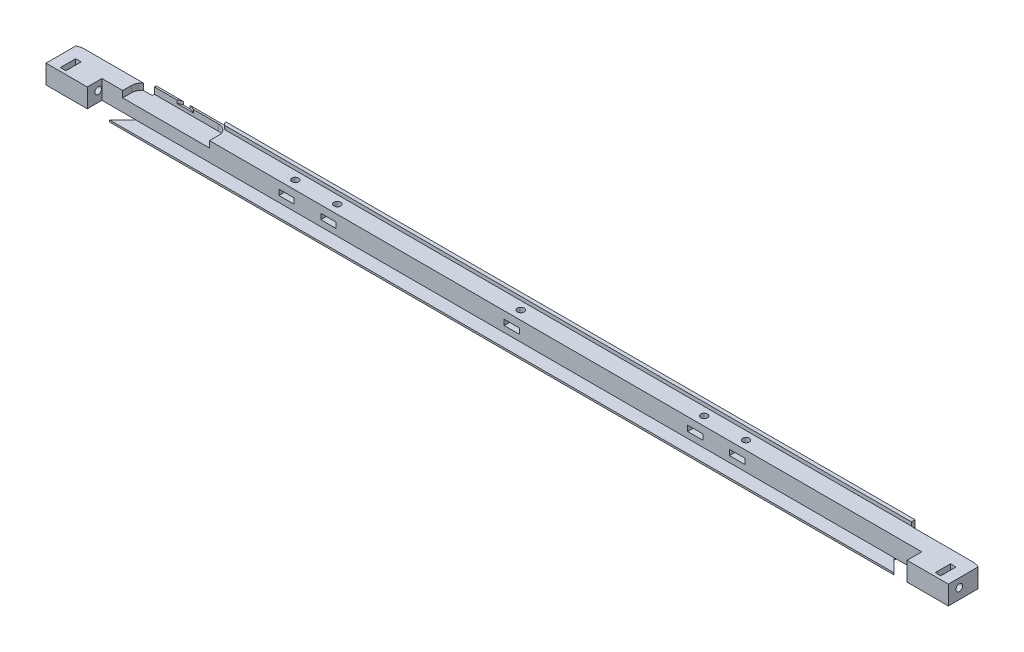
SolidWorks part; units mm, degrees
ref_plane "Front Plane" through (0, 0, 0) normal (0, 0, 1) x (1, 0, 0)
ref_plane "Top Plane" through (0, 0, 0) normal (0, 1, 0) x (1, 0, 0)
ref_plane "Right Plane" through (0, 0, 0) normal (1, 0, 0) x (0, 0, -1)
sketch "Sketch1" plane through (0, 0, 0) normal (0, 1, 0) x (1, 0, 0)
  line L0 (-134.1, 0) -> (134.1, 0)
  line L1 (134.1, 0) -> (134.1, -4.8)
  line L2 (134.1, -4.8) -> (147.6, -4.8)
  line L4 (145.3, 5.5) -> (125.16, 5.5)
  line L5 (125.16, 5.5) -> (125.16, 6.8)
  line L6 (125.16, 6.8) -> (-123.16, 6.8)
  line L7 (-123.16, 6.8) -> (-123.16, 5.5)
  line L8 (-123.16, 5.5) -> (-145.3, 5.5)
  line L10 (-147.6, -4.8) -> (-134.1, -4.8)
  line L11 (-134.1, -4.8) -> (-134.1, 0)
  line L12 (-147.6, 4.8988) -> (-147.6, -4.8)
  line L13 (147.6, 4.8988) -> (147.6, -4.8)
  line L14 (0, 6.8) -> (0, 0) construction
  line L15 (151.3, 6.8) -> (-151.3, 6.8) construction
  line L16 (151.3, 6.8) -> (151.3, -150.8147) construction
  line L17 (151.3, -150.8147) -> (-151.3, -150.8147) construction
  line L18 (-151.3, 6.8) -> (-151.3, -150.8147) construction
  line L19 (125.26, -0.1) -> (125.26, 5.5) construction
  line L20 (125.26, -0.1) -> (129.46, -4.3) construction
  line L21 (129.46, -4.3) -> (129.46, -13.8397) construction
  line L22 (-127.46, -33.4478) -> (-127.46, -4.3) construction
  line L23 (-127.46, -4.3) -> (-123.26, -0.1) construction
  line L24 (-123.26, -0.1) -> (-123.26, 5.5) construction
  arc A0 (145.3, 5.5) -> (147.6, 4.8988) centre (145.3, 0.8) cw
  arc A1 (-145.3, 5.5) -> (-147.6, 4.8988) centre (-145.3, 0.8) ccw
  dimension "D6" = 4.7
  dimension "D1" = 268.2
  dimension "D2" = 6.8
  dimension "D3" = 1.3
  dimension "D4" = 11.6
  dimension "D7" = 302.6
  dimension "D5" = 3.7
  dimension "D8" = 6
  dimension "D9" = 6
  dimension "D11" = 21.84
  dimension "D12" = 4.2
  dimension "D10" = 135
  dimension "D13" = 0.1
  dimension "D14" = 0.1
  dimension "D15" = 135
  dimension "D16" = 0.1
  dimension "D17" = 4.2
  dimension "D18" = 23.84
  dimension "D19" = 0.1
extrude "Boss-Extrude1" add sketch "Sketch1" along normal blind 8
sketch "Sketch2" plane through (0, 0, 0) normal (0, -1, 0) x (1, 0, 0)
  line L1 (125.16, -5.5) -> (147.6, -5.5)
  line L2 (125.16, -5.5) -> (125.16, 4.8)
  line L3 (125.16, 4.8) -> (147.6, 4.8)
  line L4 (147.6, -5.5) -> (147.6, 4.8)
extrude "Cut-Extrude1" cut sketch "Sketch2" against normal blind 0.6
sketch "Sketch3" plane through (0, 0, 0) normal (0, -1, 0) x (1, 0, 0)
  line L1 (-123.16, -5.5) -> (-147.6, -5.5)
  line L2 (-123.16, -5.5) -> (-123.16, 4.8)
  line L3 (-123.16, 4.8) -> (-147.6, 4.8)
  line L4 (-147.6, -5.5) -> (-147.6, 4.8)
extrude "Cut-Extrude2" cut sketch "Sketch3" against normal up to surface (0.6 mm away) up to face at (137.0084, 0.6, -0.9209)
sketch "Sketch4" plane through (0, 0, 0) normal (0, -1, 0) x (1, 0, 0)
  line L0 (129.3186, 4.3) -> (125.16, 0.1414)
  line L1 (125.16, 0.1414) -> (125.16, 0)
  line L2 (125.16, 0) -> (-123.16, 0)
  line L3 (-123.16, 0) -> (-123.16, 0.1414)
  line L4 (-123.16, 0.1414) -> (-127.3186, 4.3)
  line L5 (-127.3186, 4.3) -> (129.3186, 4.3)
  line L6 (125.26, 0.1) -> (129.46, 4.3) construction
  line L7 (129.46, 4.3) -> (129.3186, 4.3) construction
  line L8 (-123.16, 0) -> (125.16, 0) construction
  line L9 (-127.46, 4.3) -> (-123.26, 0.1) construction
  dimension "D1" = 0.1
  dimension "D2" = 0.1
extrude "Boss-Extrude2" add sketch "Sketch4" against normal up to surface (0.6 mm away) up to face at (-136.4369, 0.6, -0.9209)
sketch "Sketch5" plane through (147.6, 0, 0) normal (1, 0, 0) x (0, 0, -1)
  line L0 (6.8, 4) -> (-1.2, 4) construction
  line L1 (6.8, 8) -> (6.8, 0) construction
  line L2 (-4.8, 8) -> (-4.8, 0.6) construction
  circle A0 centre (-1.2, 4) radius 1.1
  dimension "D2" = 2.2
  dimension "D1" = 3.6
extrude "Cut-Extrude3" cut sketch "Sketch5" against normal through all
sketch "Sketch6" plane through (147.6, 0, 0) normal (1, 0, 0) x (0, 0, -1)
  line L0 (-3.7, 5.4434) -> (-3.7, 8)
  line L1 (1.3, 5.4434) -> (-1.2, 6.8868) construction
  line L2 (-1.2, 6.8868) -> (-3.7, 5.4434) construction
  line L3 (-3.7, 5.4434) -> (-3.7, 2.5566)
  line L4 (-3.7, 2.5566) -> (-1.2, 1.1132)
  line L5 (-1.2, 1.1132) -> (1.3, 2.5566)
  line L6 (1.3, 2.5566) -> (1.3, 5.4434)
  line L7 (-4.8, 8) -> (4.8988, 8) construction
  line L8 (-3.7, 8) -> (1.3, 8)
  line L9 (1.3, 8) -> (1.3, 5.4434)
  circle A0 centre (-1.2, 4) radius 2.5 construction
  dimension "D1" = 5
extrude "Cut-Extrude4" cut sketch "Sketch6" against normal blind 1.8 from offset 3.6 offset against normal yes
sketch "Sketch7" plane through (-147.6, 0, 0) normal (-1, 0, 0) x (0, 0, 1)
  line L5 (-1.3, 8) -> (-1.3, 2.5566)
  line L6 (-1.3, 2.5566) -> (1.2, 1.1132)
  line L7 (1.2, 1.1132) -> (3.7, 2.5566)
  line L8 (3.7, 2.5566) -> (3.7, 8)
  line L9 (3.7, 8) -> (-1.3, 8)
  line L10 (-1.3, 8) -> (-1.3, 2.5566)
  line L11 (-1.3, 2.5566) -> (1.2, 1.1132)
  line L12 (1.2, 1.1132) -> (3.7, 2.5566)
  line L13 (3.7, 2.5566) -> (3.7, 8)
  line L14 (3.7, 8) -> (-1.3, 8)
  dimension "D1" = 0
extrude "Cut-Extrude5" cut sketch "Sketch7" against normal blind 1.8 from offset 3.6 offset against normal yes
sketch "Sketch8" plane through (0, 8, 0) normal (0, 1, 0) x (1, 0, 0)
  line L1 (147.6, -4.8) -> (-147.6, -4.8)
  line L2 (147.6, -4.8) -> (147.6, 5.6)
  line L3 (147.6, 5.6) -> (-147.6, 5.6)
  line L4 (-147.6, -4.8) -> (-147.6, 5.6)
  line L5 (-147.6, 4.8988) -> (-147.6, -4.8) construction
  line L6 (125.16, 6.8) -> (-123.16, 6.8) construction
  dimension "D1" = 1.2
extrude "Cut-Extrude6" cut sketch "Sketch8" against normal blind 1.2
sketch "Sketch9" plane through (0, 6.8, 0) normal (0, 1, 0) x (1, 0, 0)
  line L0 (-151.3, 6.8) -> (-151.3, -150.8147) construction
  line L1 (-73.7, 0.0132) -> (-71.2, 1.4566) construction
  line L2 (-71.2, 1.4566) -> (-71.2, 4.3434)
  line L3 (-71.2, 4.3434) -> (-73.7, 5.7868)
  line L4 (-73.7, 5.7868) -> (-76.2, 4.3434)
  line L5 (-76.2, 4.3434) -> (-76.2, 1.4566)
  line L6 (-76.2, 1.4566) -> (-73.7, 0.0132) construction
  line L7 (-134.1, 0) -> (134.1, 0) construction
  line L8 (-71.2, 1.4566) -> (-71.2, 0)
  line L9 (-71.2, 0) -> (-76.2, 0)
  line L10 (-76.2, 0) -> (-76.2, 1.4566)
  line L11 (151.3, 6.8) -> (151.3, -150.8147) construction
  line L12 (73.7, 0.0132) -> (76.2, 1.4566) construction
  line L13 (76.2, 1.4566) -> (76.2, 4.3434)
  line L14 (76.2, 4.3434) -> (73.7, 5.7868)
  line L15 (73.7, 5.7868) -> (71.2, 4.3434)
  line L16 (71.2, 4.3434) -> (71.2, 1.4566)
  line L17 (71.2, 1.4566) -> (73.7, 0.0132) construction
  line L18 (71.2, 1.4566) -> (71.2, 0)
  line L19 (71.2, 0) -> (76.2, 0)
  line L20 (76.2, 0) -> (76.2, 1.4566)
  line L21 (-73.7, 2.9) -> (-60, 2.9) construction
  line L22 (-57.5, 1.4566) -> (-57.5, 4.3434)
  line L23 (-57.5, 4.3434) -> (-60, 5.7868)
  line L24 (-60, 5.7868) -> (-62.5, 4.3434)
  line L25 (-62.5, 4.3434) -> (-62.5, 1.4566)
  line L26 (-62.5, 1.4566) -> (-60, 0.0132) construction
  line L27 (-60, 0.0132) -> (-57.5, 1.4566) construction
  line L28 (0, 0.0132) -> (2.5, 1.4566) construction
  line L29 (2.5, 1.4566) -> (2.5, 4.3434)
  line L30 (2.5, 4.3434) -> (0, 5.7868)
  line L31 (0, 5.7868) -> (-2.5, 4.3434)
  line L32 (-2.5, 4.3434) -> (-2.5, 1.4566)
  line L33 (-2.5, 1.4566) -> (0, 0.0132) construction
  line L34 (60, 0.0132) -> (62.5, 1.4566) construction
  line L35 (62.5, 1.4566) -> (62.5, 4.3434)
  line L36 (62.5, 4.3434) -> (60, 5.7868)
  line L37 (60, 5.7868) -> (57.5, 4.3434)
  line L38 (57.5, 4.3434) -> (57.5, 1.4566)
  line L39 (57.5, 1.4566) -> (60, 0.0132) construction
  line L40 (-60, 2.9) -> (0, 2.9) construction
  line L41 (0, 2.9) -> (60, 2.9) construction
  line L42 (60, 2.9) -> (73.7, 2.9) construction
  line L43 (-62.5, 1.4566) -> (-62.5, 0)
  line L44 (-134.1, 0) -> (134.1, 0) construction
  line L45 (-62.5, 0) -> (-57.5, 0)
  line L46 (-57.5, 0) -> (-57.5, 1.4566)
  line L47 (-2.5, 1.4566) -> (-2.5, 0)
  line L48 (-123.16, 0) -> (125.16, 0) construction
  line L49 (-2.5, 0) -> (2.5, 0)
  line L50 (2.5, 0) -> (2.5, 1.4566)
  line L51 (62.5, 1.4566) -> (62.5, 0)
  line L52 (62.5, 0) -> (57.5, 0)
  line L53 (57.5, 0) -> (57.5, 1.4566)
  circle A0 centre (-73.7, 2.9) radius 2.5 construction
  circle A1 centre (73.7, 2.9) radius 2.5 construction
  circle A2 centre (-60, 2.9) radius 2.5 construction
  circle A3 centre (0, 2.9) radius 2.5 construction
  circle A4 centre (60, 2.9) radius 2.5 construction
  dimension "D1" = 5
  dimension "D2" = 77.6
  dimension "D3" = 2.9
  dimension "D4" = 77.6
  dimension "D5" = 2.9
  dimension "D6" = 60
extrude "Cut-Extrude7" cut sketch "Sketch9" against normal blind 1.8 from offset 2.4 offset against normal yes
sketch "Sketch10" plane through (0, 6.8, 0) normal (0, 1, 0) x (1, 0, 0)
  circle A0 centre (-73.7, 2.9) radius 1.1
  circle A1 centre (73.7, 2.9) radius 1.1
  circle A2 centre (60, 2.9) radius 1.1
  circle A3 centre (0, 2.9) radius 1.1
  circle A4 centre (-60, 2.9) radius 1.1
  dimension "D1" = 2.2
extrude "Cut-Extrude8" cut sketch "Sketch10" against normal blind 5
sketch "Sketch11" plane through (0, 4.4, 0) normal (0, -1, 0) x (1, 0, 0)
  line L0 (-76.2, -4.3434) -> (-76.2, 0) construction
  line L1 (76.2, -1.8) -> (71.2, -1.8)
  line L2 (76.2, -1.8) -> (76.2, -4)
  line L3 (76.2, -4) -> (71.2, -4)
  line L4 (71.2, -1.8) -> (71.2, -4)
  line L5 (62.5, -1.8) -> (57.5, -1.8)
  line L6 (62.5, -1.8) -> (62.5, -4)
  line L7 (62.5, -4) -> (57.5, -4)
  line L8 (57.5, -1.8) -> (57.5, -4)
  line L9 (2.5, -1.8) -> (-2.5, -1.8)
  line L10 (2.5, -1.8) -> (2.5, -4)
  line L11 (2.5, -4) -> (-2.5, -4)
  line L12 (-2.5, -1.8) -> (-2.5, -4)
  line L13 (-57.5, -1.8) -> (-62.5, -1.8)
  line L14 (-57.5, -1.8) -> (-57.5, -4)
  line L15 (-57.5, -4) -> (-62.5, -4)
  line L16 (-62.5, -1.8) -> (-62.5, -4)
  line L17 (-71.2, -1.8) -> (-76.2, -1.8)
  line L18 (-71.2, -1.8) -> (-71.2, -4)
  line L19 (-71.2, -4) -> (-76.2, -4)
  line L20 (-76.2, -1.8) -> (-76.2, -4)
  line L22 (-57.5, 0) -> (-57.5, -4.3434) construction
  line L24 (2.5, 0) -> (2.5, -4.3434) construction
  line L26 (-2.5, -4.3434) -> (-2.5, 0) construction
  line L28 (-62.5, -4.3434) -> (-62.5, 0) construction
  line L30 (-71.2, 0) -> (-71.2, -4.3434) construction
  line L31 (62.5, 0) -> (62.5, -4.3434) construction
  line L32 (76.2, 0) -> (76.2, -4.3434) construction
  line L33 (71.2, -4.3434) -> (71.2, 0) construction
  line L34 (57.5, -4.3434) -> (57.5, 0) construction
  circle A0 centre (73.7, -2.9) radius 1.1 construction
  circle A1 centre (60, -2.9) radius 1.1 construction
  circle A2 centre (0, -2.9) radius 1.1 construction
  circle A3 centre (-60, -2.9) radius 1.1 construction
  circle A4 centre (-73.7, -2.9) radius 1.1 construction
extrude "Cut-Extrude9" cut sketch "Sketch11" against normal blind 0.2
sketch "Sketch12" plane through (0, 4.6, 0) normal (0, -1, 0) x (-1, 0, 0)
  line L0 (73.7, 4) -> (71.2, 4) construction
  line L1 (72.6, 4) -> (74.8, 4)
  line L2 (72.6, 4) -> (72.6, 1.8)
  line L3 (72.6, 1.8) -> (74.8, 1.8)
  line L4 (74.8, 4) -> (74.8, 1.8)
  line L5 (71.2, 1.8) -> (76.2, 1.8) construction
  line L6 (60, 4) -> (57.5, 4) construction
  line L7 (58.9, 4) -> (61.1, 4)
  line L8 (58.9, 4) -> (58.9, 1.8)
  line L9 (58.9, 1.8) -> (61.1, 1.8)
  line L10 (61.1, 4) -> (61.1, 1.8)
  line L11 (57.5, 1.8) -> (62.5, 1.8) construction
  line L12 (0, 4) -> (-2.5, 4) construction
  line L13 (-1.1, 4) -> (1.1, 4)
  line L14 (-1.1, 4) -> (-1.1, 1.8)
  line L15 (-1.1, 1.8) -> (1.1, 1.8)
  line L16 (1.1, 4) -> (1.1, 1.8)
  line L17 (-2.5, 1.8) -> (2.5, 1.8) construction
  line L18 (-60, 4) -> (-62.5, 4) construction
  line L19 (-61.1, 4) -> (-58.9, 4)
  line L20 (-61.1, 4) -> (-61.1, 1.8)
  line L21 (-61.1, 1.8) -> (-58.9, 1.8)
  line L22 (-58.9, 4) -> (-58.9, 1.8)
  line L23 (-62.5, 1.8) -> (-57.5, 1.8) construction
  line L24 (-71.2, 4) -> (-73.7, 4) construction
  line L25 (-72.6, 4) -> (-74.8, 4)
  line L26 (-72.6, 4) -> (-72.6, 1.8)
  line L27 (-72.6, 1.8) -> (-74.8, 1.8)
  line L28 (-74.8, 4) -> (-74.8, 1.8)
  line L29 (-76.2, 1.8) -> (-71.2, 1.8) construction
  arc A0 (73.7, 1.8) -> (73.7, 4) centre (73.7, 2.9) ccw construction
  arc A1 (73.7, 4) -> (73.7, 1.8) centre (73.7, 2.9) ccw construction
  arc A2 (60, 1.8) -> (60, 4) centre (60, 2.9) ccw construction
  arc A3 (60, 4) -> (60, 1.8) centre (60, 2.9) ccw construction
  arc A4 (0, 1.8) -> (0, 4) centre (0, 2.9) ccw construction
  arc A5 (0, 4) -> (0, 1.8) centre (0, 2.9) ccw construction
  arc A6 (-60, 1.8) -> (-60, 4) centre (-60, 2.9) ccw construction
  arc A7 (-60, 4) -> (-60, 1.8) centre (-60, 2.9) ccw construction
  arc A8 (-73.7, 4) -> (-73.7, 1.8) centre (-73.7, 2.9) ccw construction
  arc A9 (-73.7, 1.8) -> (-73.7, 4) centre (-73.7, 2.9) ccw construction
extrude "Cut-Extrude10" cut sketch "Sketch12" against normal blind 0.2
sketch "Sketch13" plane through (0, 8, 0) normal (0, 1, 0) x (1, 0, 0)
  line L0 (125.16, 6.8) -> (-123.16, 6.8) construction
  line L1 (125.16, 5.6) -> (-123.16, 5.6) construction
  line L2 (-100.3, 6.8) -> (-123.16, 6.8)
  line L3 (-123.16, 6.8) -> (-123.16, 5.5)
  line L4 (-123.16, 5.5) -> (-99.1, 5.6)
  line L5 (-151.3, 6.8) -> (-151.3, -150.8147) construction
  arc A0 (-100.3, 6.8) -> (-99.1, 5.6) centre (-99.1, 6.8) ccw
  dimension "D1" = 52.2
extrude "Cut-Extrude11" cut sketch "Sketch13" against normal blind 1.2
sketch "Sketch14" plane through (0, 6.8, 0) normal (0, 1, 0) x (1, 0, 0)
  line L0 (-98.9, 0) -> (-127.3, 0)
  line L1 (-134.1, 0) -> (134.1, 0) construction
  line L2 (-127.3, 0) -> (-127.3, 2.9)
  line L3 (-102.1, 6.2) -> (-123.9, 6.2)
  line L4 (-98.9, 3.1) -> (-98.9, 0)
  line L7 (-151.3, 6.8) -> (-151.3, -150.8147) construction
  line L8 (-100.3, 6.8) -> (-123.16, 6.8) construction
  ellipse E0 centre (-123.9, 2.9) end of major axis (-127.3, 2.9) minor radius 3.3 (-127.3, 2.9) -> (-123.9, 6.2) cw
  ellipse E1 centre (-102.1, 3.1) end of major axis (-105.3, 3.1) minor radius 3.1 (-98.9, 3.1) -> (-102.1, 6.2) ccw
  point P10 (0, 0)
  dimension "D1" = 28.4
  dimension "D2" = 24
  dimension "D3" = 3.3
  dimension "D4" = 3.4
  dimension "D5" = 3.1
  dimension "D6" = 3.2
  dimension "D7" = 0.6
extrude "Cut-Extrude12" cut sketch "Sketch14" against normal offset from surface (2.1 mm away) 3.3 up to face at (12.6679, 8, -6.1379)
sketch "Sketch15" plane through (0, 4.7, 0) normal (0, 1, 0) x (1, 0, 0)
  line L0 (-102.1, 6.2) -> (-123.16, 6.2) construction
  line L3 (-127.3, 2.9) -> (-127.3, 0) construction
  circle A0 centre (-113.1, 1.3) radius 5.6
  point P6 (-127.3, 0.9771)
  dimension "D1" = 11.2
  dimension "D2" = 4.9
  dimension "D3" = 14.2
extrude "Cut-Extrude13" cut sketch "Sketch15" along normal up to surface (1 mm away) from offset 1.1 up to face at (-136.2052, 6.8, -1.1866)
equation "\"LCD_Height\"= 158mm"
equation "\"LCD_Width\"= 268mm"
equation "\"LCD_PCB_Height\"= 10mm"
equation "\"LCD_PCB_Width\"= 189"
equation "\"LCD_PCB_LOff\"= 38.5"
equation "\"LCD_Thick\"= 2.9mm"
equation "\"LCD_TBezel\"= 4.6mm"
equation "\"LCD_LBezel\"= 4.94mm"
equation "\"LCD_RBezel\"= 6.94mm"
equation "\"LCD_BBezel\"= 9.4mm"
equation "\"Wing_Height\"= 11.5mm"
equation "\"Wing_Width\"= 5mm"
equation "\"Wing_Corner\"= 1mm"
equation "\"Wing_Hole_VOff\"= 3.5mm"
equation "\"Wing_Hole_HOff\"= 2.8mm"
equation "\"Wing_Spacing\"= 128.9 + 2 * \"Wing_Hole_VOff\" - \"Wing_Height\""
equation "\"Wing_TOff\"= 8.35 - \"Wing_Hole_VOff\""
equation "\"Wing_DOff\"= 0.7mm"
equation "\"Wing_Thick\"= 0.3mm"
equation "\"Print_Gap\"= 0.2mm"
equation "\"Pin1_Pos\"= 89.75mm"
equation "\"Pin_Space\"= 0.5mm"
equation "\"Pin_num\"= 30"
equation "\"Min_Thick\"= 1.2mm"
equation "\"Nut_Width\"= 4.8mm"
equation "\"Nut_Height\"= 5.6mm"
equation "\"Nut_Thick\"= 1.6mm"
equation "\"Screw_Hole\"= 2.2mm"
equation "\"Screw_Chamf\"= 0.9mm"
equation "\"Bezel_Gap\"= 0.4mm"
equation "\"D1@Sketch1\"=\"LCD_Width\" + \"Print_Gap\""
equation "\"D2@Sketch1\"= \"Min_Thick\" + \"Nut_Height\""
equation "\"D3@Sketch1\"=\"Min_Thick\" + \"Print_Gap\" / 2"
equation "\"D4@Sketch1\"= 6 + \"Screw_Hole\"/2 + \"Screw_Chamf\" + \"Nut_Width\"/2 + \"Min_Thick\""
equation "\"D6@Sketch1\"=\"Corner_Radius\" - \"Min_Thick\" - \"Print_Gap\" / 2"
equation "\"D7@Sketch1\"= \"LCD_Width\" + 2 * 16 + 2 * \"Min_Thick\" + \"Print_Gap\""
equation "\"D5@Sketch1\"=3 * \"Min_Thick\" + \"Print_Gap\" / 2"
equation "\"D11@Sketch1\"=\"Min_Thick\" + \"USB_Width\" + \"Print_Gap\" / 2 + \"LCD_LBezel\" - \"Bezel_Gap\""
equation "\"D12@Sketch1\"=\"LCD_TBezel\" - \"Bezel_Gap\""
equation "\"D13@Sketch1\"=\"Print_Gap\" / 2"
equation "\"D14@Sketch1\"=\"Print_Gap\" / 2"
equation "\"D16@Sketch1\"=\"Print_Gap\" / 2"
equation "\"D17@Sketch1\"=\"LCD_TBezel\" - \"Bezel_Gap\""
equation "\"D18@Sketch1\"=\"Min_Thick\" + \"USB_Width\" + \"LCD_RBezel\" + \"Print_Gap\" / 2 - \"Bezel_Gap\""
equation "\"D19@Sketch1\"=\"Print_Gap\" / 2"
equation "\"D1@Sketch4\"=\"Print_Gap\" /2"
equation "\"D2@Sketch4\"= \"Print_Gap\" / 2"
equation "\"USB_Width\"= 16mm"
equation "\"Corner_Radius\"= 6mm"
equation "\"D8@Sketch1\"=\"Corner_Radius\""
equation "\"D9@Sketch1\"=\"Corner_Radius\""
equation "\"D1@Sketch5\"= \"Min_Thick\" + \"Nut_Width\" / 2"
equation "\"D2@Sketch5\"=\"Screw_Hole\""
equation "\"D1@Sketch6\"=\"Nut_Width\" + \"Print_Gap\""
equation "\"D1@Cut-Extrude4\"=\"Nut_Thick\" + \"Print_Gap\""
equation "\"D19@Cut-Extrude4\"=\"Min_Thick\" * 3"
equation "\"D1@Cut-Extrude5\"=\"Nut_Thick\" + \"Print_Gap\""
equation "\"D19@Cut-Extrude5\"=3 * \"Min_Thick\""
equation "\"D1@Sketch8\"= \"Min_Thick\""
equation "\"D1@Cut-Extrude6\"=\"Min_Thick\""
equation "\"D1@Sketch9\"=\"Nut_Width\" + \"Print_Gap\""
equation "\"D3@Sketch9\"=(\"Nut_Height\" + \"Print_Gap\")/2"
equation "\"D1@Cut-Extrude7\"=\"Nut_Thick\" + \"Print_Gap\""
equation "\"D19@Cut-Extrude7\"=\"Min_Thick\"  * 2"
equation "\"D2@Sketch9\"= 80 - \"Nut_Width\" / 2"
equation "\"D4@Sketch9\"=80 - \"Nut_Width\" / 2"
equation "\"D5@Sketch9\"=(\"Nut_Height\" + \"Print_Gap\") / 2"
equation "\"D1@Sketch10\"=\"Screw_Hole\""
equation "\"D1@Cut-Extrude9\"= \"Print_Gap\""
equation "\"D1@Cut-Extrude10\"= \"Print_Gap\""
equation "\"D1@Sketch13\"=24 + \"Print_Gap\" + 64 - 36"
equation "\"D1@Cut-Extrude11\"=\"Min_Thick\""
equation "\"D1@Sketch14\"=2 * \"Print_Gap\" + 64 - 36"
equation "\"D2@Sketch14\"=24"
equation "\"D3@Sketch14\"=3.2 + \"Print_Gap\" / 2"
equation "\"D4@Sketch14\"=3.2 + \"Print_Gap\""
equation "\"D5@Sketch14\"=3 + \"Print_Gap\" / 2"
equation "\"D6@Sketch14\"=3 + \"Print_Gap\""
equation "\"D1@Sketch15\"=10.8 + 2 * \"Print_Gap\""
equation "\"D2@Sketch15\"=\"Print_Gap\" / 2 + 40.8 -36"
equation "\"D3@Sketch15\"=50 - 36 + \"Print_Gap\""
equation "\"D7@Sketch14\"=\"Min_Thick\" / 2"
